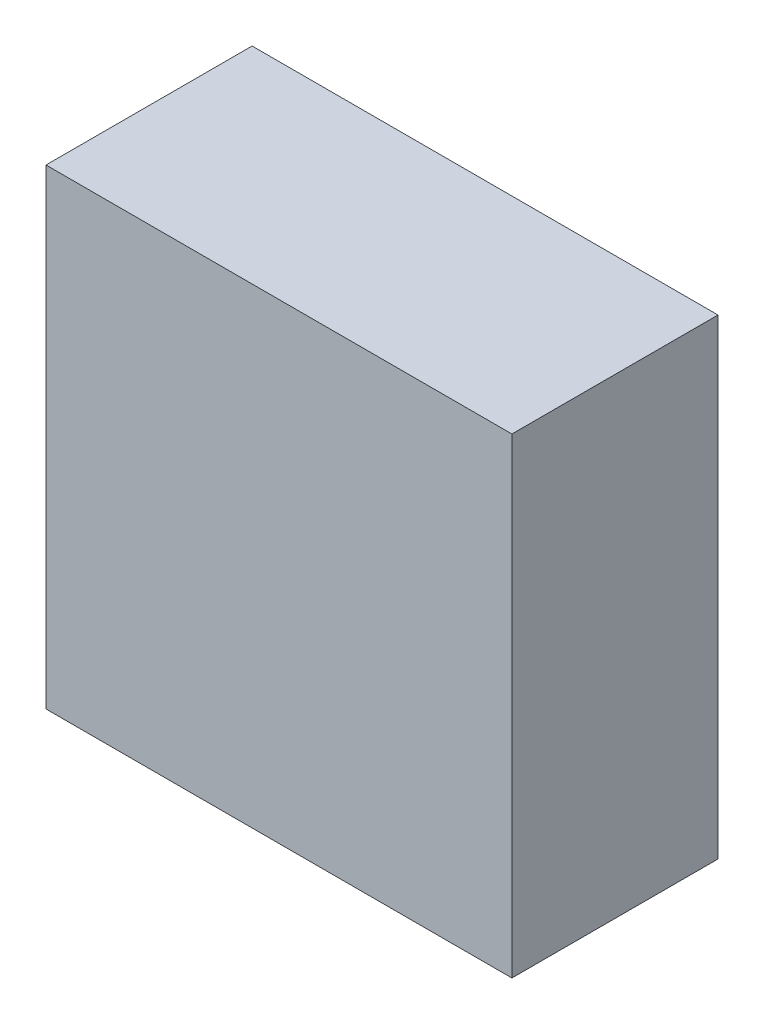
SolidWorks part; units mm, degrees
ref_plane "Front Plane" through (0, 0, 0) normal (0, 0, 1) x (1, 0, 0)
ref_plane "Top Plane" through (0, 0, 0) normal (0, 1, 0) x (1, 0, 0)
ref_plane "Right Plane" through (0, 0, 0) normal (1, 0, 0) x (0, 0, -1)
sketch "Sketch1" plane through (0, 0, 0) normal (0, 0, 1) x (1, 0, 0)
  line L0 (0, 2.286) -> (2.2606, 2.286)
  line L1 (2.2606, 2.286) -> (2.2606, 0)
  line L2 (2.2606, 0) -> (0, 0)
  line L3 (0, 0) -> (0, 2.286)
extrude "Component_Outline" add sketch "Sketch1" along normal blind 1 separate body
sketch3d "3DSketch1"
  line L0 (0, 0, 0) -> (1, 0, 0)
  line L1 (0, 0, 0) -> (0, 1, 0)
  line L2 (0, 0, 0) -> (0, 0, 1)
  point P0 (0, 0, 0)
